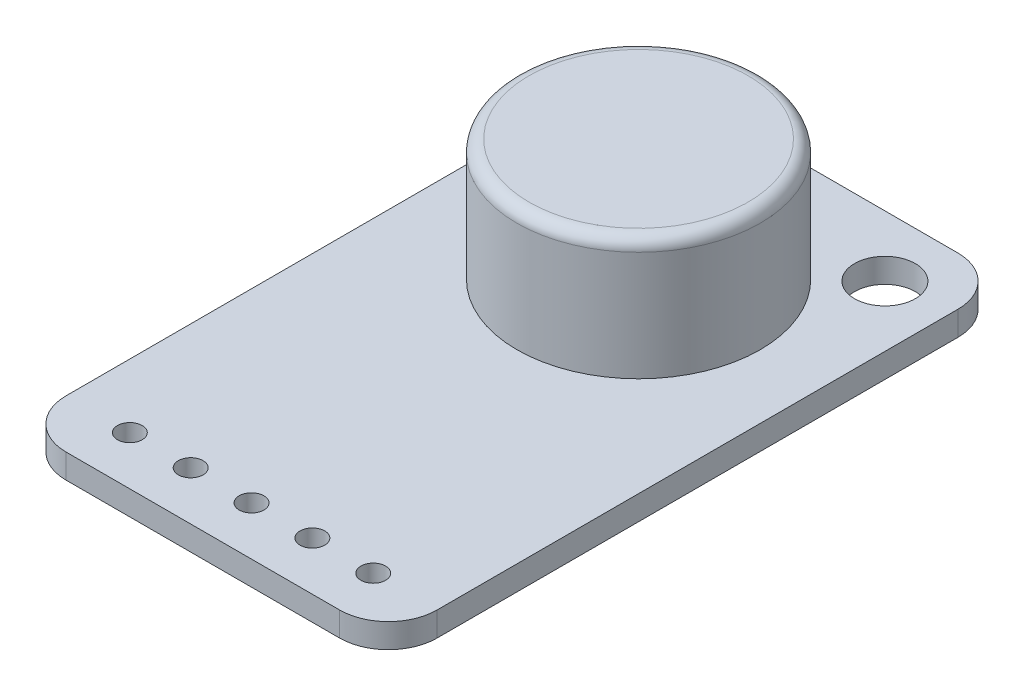
SolidWorks part; units mm, degrees
ref_plane "Front Plane" through (0, 0, 0) normal (0, 0, 1) x (1, 0, 0)
ref_plane "Top Plane" through (0, 0, 0) normal (0, 1, 0) x (1, 0, 0)
ref_plane "Right Plane" through (0, 0, 0) normal (1, 0, 0) x (0, 0, -1)
sketch "Sketch1" plane through (0, 0, 0) normal (0, 1, 0) x (1, 0, 0)
  line L1 (0, 0) -> (-15.24, 0)
  line L2 (0, 0) -> (0, 25.4)
  line L3 (0, 25.4) -> (-15.24, 25.4)
  line L4 (-15.24, 0) -> (-15.24, 25.4)
  dimension "D1" = 15.24
  dimension "D2" = 25.4
extrude "Boss-Extrude1" add sketch "Sketch1" along normal blind 1
fillet "Fillet1" radius 2 4 edges at (-15.24, 0.5, 0) (0, 0.5, 0) (-15.24, 0.5, -25.4) (0, 0.5, -25.4)
sketch "Sketch2" plane through (0, 1, 0) normal (0, 1, 0) x (1, 0, 0)
  line L0 (-15.24, 23.4) -> (-15.24, 2) construction
  line L1 (-2, 25.4) -> (-13.24, 25.4) construction
  line L2 (0, 2) -> (0, 23.4) construction
  line L3 (-13.24, 0) -> (-2, 0) construction
  circle A0 centre (-2.5, 22.9) radius 1.25
  circle A1 centre (-12.74, 22.9) radius 1.25
  circle A2 centre (-12.62, 2) radius 0.508
  circle A3 centre (-10.12, 2) radius 0.508
  circle A4 centre (-7.62, 2) radius 0.508
  circle A5 centre (-5.12, 2) radius 0.508
  circle A6 centre (-2.62, 2) radius 0.508
  dimension "D1" = 2.5
  dimension "D2" = 2.5
  dimension "D3" = 2.5
  dimension "D4" = 2.5
  dimension "D5" = 2.5
  dimension "D6" = 2.5
  dimension "D7" = 1.016
  dimension "D8" = 2
  dimension "D9" = 5
  dimension "D10" = 2.62
extrude "Cut-Extrude1" cut sketch "Sketch2" against normal blind 1
sketch "Sketch3" plane through (0, 1, 0) normal (0, 1, 0) x (1, 0, 0)
  line L0 (0, 2) -> (0, 23.4) construction
  line L2 (-2, 25.4) -> (-13.24, 25.4) construction
  circle A0 centre (-7.62, 17.9) radius 5
  dimension "D1" = 7.62
  dimension "D2" = 7.5
  dimension "D3" = 10
extrude "Boss-Extrude2" add sketch "Sketch3" along normal blind 5
fillet "Fillet2" radius 0.5 1 edges at (-7.62, 6, -12.9)
